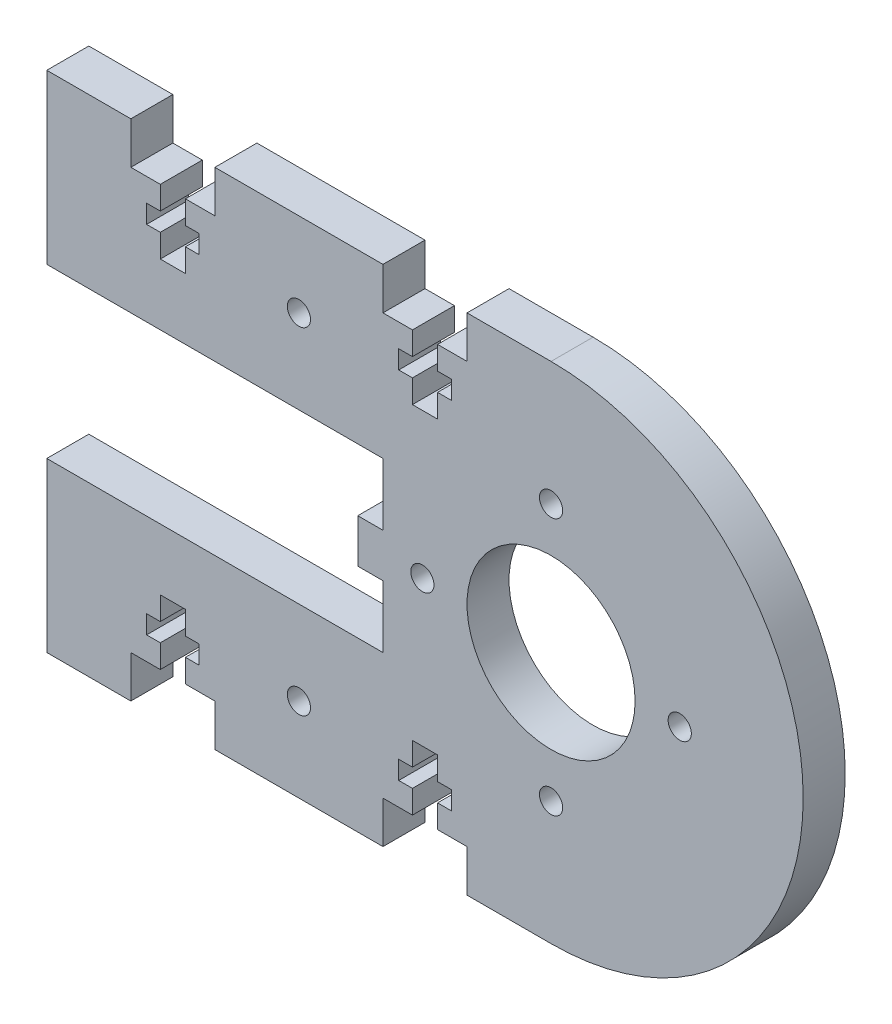
SolidWorks part; units mm, degrees
material "Beech"
ref_plane "Front Plane" through (0, 0, 0) normal (0, 0, 1) x (1, 0, 0)
ref_plane "Top Plane" through (0, 0, 0) normal (0, 1, 0) x (1, 0, 0)
ref_plane "Right Plane" through (0, 0, 0) normal (1, 0, 0) x (0, 0, -1)
sketch "Sketch1" plane through (0, 0, 0) normal (0, 0, 1) x (1, 0, 0)
  line L1 (-38.1, -38.1) -> (38.1, -38.1)
  line L2 (-38.1, -38.1) -> (-38.1, 38.1)
  line L3 (-38.1, 38.1) -> (38.1, 38.1)
  line L5 (-38.1, -38.1) -> (38.1, 38.1) construction
  line L6 (-38.1, 38.1) -> (38.1, -38.1) construction
  arc A0 (38.1, 38.1) -> (38.1, -38.1) centre (38.1, 0) cw
  point P0 (0, 0)
  dimension "D1" = 76.2
  dimension "D2" = 76.2
extrude "Boss-Extrude1" add sketch "Sketch1" along normal blind 6.35 contours L3 A0 L1 L2
sketch "Sketch2" plane through (0, 0, 6.35) normal (0, 0, 1) x (1, 0, 0)
  line L0 (-38.1, 0) -> (12.7, 0) construction
  line L1 (-38.1, 12.7) -> (12.7, 12.7)
  line L2 (-38.1, 12.7) -> (-38.1, -12.7)
  line L3 (-38.1, -12.7) -> (12.7, -12.7)
  line L4 (12.7, 12.7) -> (12.7, -12.7)
  line L5 (-38.1, -38.1) -> (-38.1, 38.1) construction
  point P0 (0, 0)
  dimension "D1" = 25.4
  dimension "D2" = 12.7
extrude "Cut-Extrude1" cut sketch "Sketch2" against normal through all
sketch "Sketch3" plane through (0, 0, 6.35) normal (0, 0, 1) x (1, 0, 0)
  line L0 (-38.1, -38.1) -> (38.1, -38.1) construction
  line L1 (-25.4, -38.1) -> (-12.7, -38.1)
  line L2 (-25.4, -38.1) -> (-25.4, -31.75)
  line L3 (-25.4, -31.75) -> (-20.9486, -31.75)
  line L4 (-12.7, -38.1) -> (-12.7, -31.75)
  line L6 (-19.05, -38.1) -> (11.43, -38.1) construction
  line L7 (-19.05, -38.1) -> (-19.05, -21.971) construction
  line L8 (-17.1514, -25.4714) -> (-17.1513, -21.971)
  line L9 (-15.0812, -25.4714) -> (-17.1514, -25.4714)
  line L10 (0, 0) -> (42.8175, 0) construction
  line L11 (-15.0812, -28.2496) -> (-15.0812, -25.4714)
  line L12 (-17.1514, -28.2496) -> (-15.0812, -28.2496)
  line L13 (-17.1514, -31.75) -> (-17.1514, -28.2496)
  line L14 (-17.1514, -31.75) -> (-12.7, -31.75)
  line L21 (-17.1513, -21.971) -> (-20.9486, -21.971)
  line L22 (-20.9486, -31.75) -> (-20.9486, -28.2496)
  line L23 (-20.9486, -28.2496) -> (-23.0187, -28.2496)
  line L24 (-23.0187, -28.2496) -> (-23.0187, -25.4714)
  line L25 (-23.0187, -25.4714) -> (-20.9486, -25.4714)
  line L26 (-20.9486, -25.4714) -> (-20.9486, -21.971)
  dimension "D1" = 6.35
  dimension "D2" = 3.7973
  dimension "D3" = 12.7
  dimension "D4" = 2.7781
  dimension "D5" = 9.779
  dimension "D6" = 3.9688
  dimension "D17" = 12.7
extrude "Cut-Extrude2" cut sketch "Sketch3" against normal blind 6.35
sketch "Sketch4" plane through (0, 0, 6.35) normal (0, 0, 1) x (1, 0, 0)
  line L2 (0, 0) -> (0, -25.4) construction
  circle A3 centre (0, -25.4) radius 1.7526
  point P16 (0, 0)
  dimension "D1" = 25.4
  dimension "D2" = 3.5052
pattern_linear "LPattern1" count 2 spacing 38.1 along (1, 0, 0) of "Cut-Extrude2"
extrude "Cut-Extrude5" cut sketch "Sketch4" against normal through all
sketch "Sketch6" plane through (12.7, 0, 0) normal (-1, 0, 0) x (0, 0, 1)
  line L0 (0, 0) -> (6.35, 0) construction
  line L1 (0, -12.7) -> (0, 12.7) construction
  line L2 (6.35, -12.7) -> (6.35, 12.7) construction
  line L4 (0, 3.302) -> (6.35, 3.302)
  line L5 (0, 3.302) -> (0, -3.302)
  line L6 (0, -3.302) -> (6.35, -3.302)
  line L7 (6.35, 3.302) -> (6.35, -3.302)
  line L8 (0, 3.302) -> (6.35, -3.302) construction
  line L9 (0, -3.302) -> (6.35, 3.302) construction
  point P6 (3.175, 0)
  dimension "D1" = 6.604
extrude "Boss-Extrude2" add sketch "Sketch6" along normal blind 3.81
ref_plane "Plane1" through (0, 0, 0) normal (1, 0, 0) x (0, 0, -1)
mirror "Mirror3" about plane through (0, 0, 0) normal (0, 1, 0) of "Cut-Extrude5"
ref_plane "Plane2" through (0, 0, 3.175) normal (0, 0, 1) x (1, 0, 0)
mirror "Mirror4" about plane through (0, 0, 0) normal (0, 1, 0) of "LPattern1", "Cut-Extrude2"
sketch "Sketch5" plane through (0, 0, 6.35) normal (0, 0, 1) x (1, 0, 0)
  line L1 (0, 0) -> (38.1, 0) construction
  circle A0 centre (38.1, 0) radius 12.7
  circle A5 centre (38.1, 0) radius 19.4437 construction
  point P9 (38.1, 0)
  point P16 (38.1, 0)
  dimension "D1" = 25.4
  dimension "D5" = 38.8874
extrude "Cut-Extrude4" cut sketch "Sketch5" against normal through all
sketch "Sketch7" plane through (0, 0, 6.35) normal (0, 0, 1) x (1, 0, 0)
  line L0 (38.1, -19.4437) -> (38.1, 19.4437) construction
  circle A0 centre (38.1, 0) radius 12.7 construction
  circle A1 centre (38.1, 0) radius 12.7 construction
  circle A2 centre (38.1, 19.4437) radius 1.7526
  dimension "D2" = 3.5052
  dimension "D1" = 38.8874
extrude "Cut-Extrude6" cut sketch "Sketch7" against normal through all
pattern_circular "CirPattern1" count 4 over 360 about axis through (38.1, 0, 0) along (0, 0, 1) of "Cut-Extrude6"
sketch "Sketch8" [suppressed] plane through (0, 0, 6.35) normal (0, 0, 1) x (1, 0, 0)
  line L0 (38.1, 9) -> (38.1, -9) construction
  circle A0 centre (38.1, 0) radius 6
  arc A1 (38.1, -38.1) -> (38.1, 38.1) centre (38.1, 0) ccw construction
  circle A2 centre (38.1, 9) radius 1.5
  circle A3 centre (38.1, -9) radius 1.5
  dimension "D1" = 12
  dimension "D3" = 3
  dimension "D2" = 18
extrude "Cut-Extrude7" [suppressed] cut sketch "Sketch8" against normal through all
